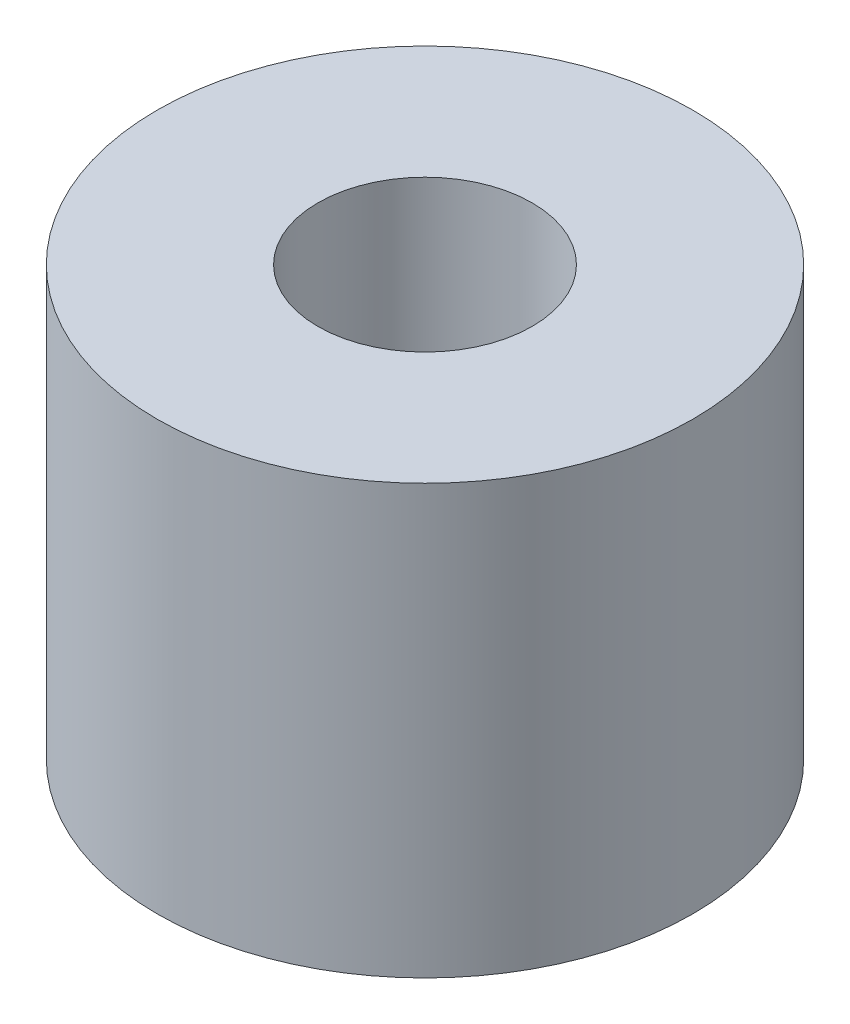
SolidWorks part; units mm, degrees
ref_plane "Front Plane" through (0, 0, 0) normal (0, 0, 1) x (1, 0, 0)
ref_plane "Top Plane" through (0, 0, 0) normal (0, 1, 0) x (1, 0, 0)
ref_plane "Right Plane" through (0, 0, 0) normal (1, 0, 0) x (0, 0, -1)
sketch "Sketch1" plane through (0, 0, 0) normal (0, 1, 0) x (1, 0, 0)
  circle A0 centre (0, 0) radius 2.5
  dimension "D1" = 5
extrude "Boss-Extrude1" add sketch "Sketch1" along normal blind 4
sketch "Sketch2" plane through (0, 4, 0) normal (0, 1, 0) x (1, 0, 0)
  circle A0 centre (0, 0) radius 1
  dimension "D1" = 2
extrude "Cut-Extrude1" cut sketch "Sketch2" against normal through all
